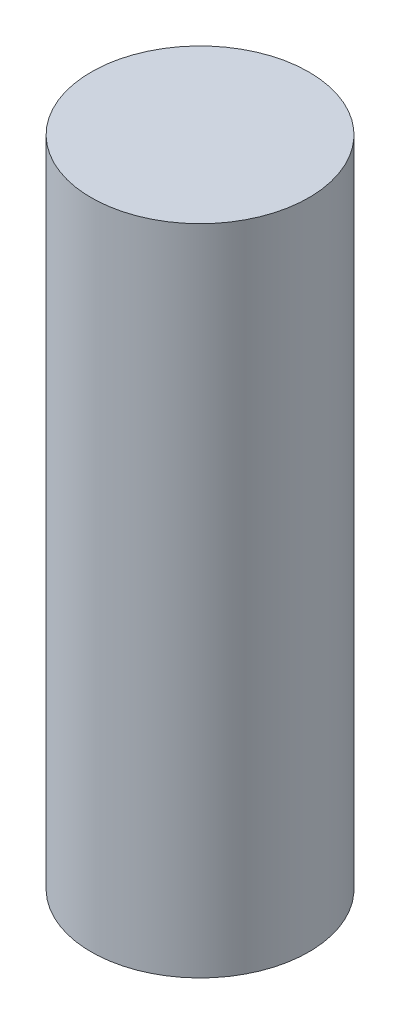
SolidWorks part; units mm, degrees
ref_plane "Front Plane" through (0, 0, 0) normal (0, 0, 1) x (1, 0, 0)
ref_plane "Top Plane" through (0, 0, 0) normal (0, 1, 0) x (1, 0, 0)
ref_plane "Right Plane" through (0, 0, 0) normal (1, 0, 0) x (0, 0, -1)
sketch "Sketch1" plane through (0, 0, 0) normal (0, 1, 0) x (1, 0, 0)
  circle A0 centre (0, 0) radius 50.8
extrude "Boss-Extrude1" add sketch "Sketch1" along normal blind 304.8
